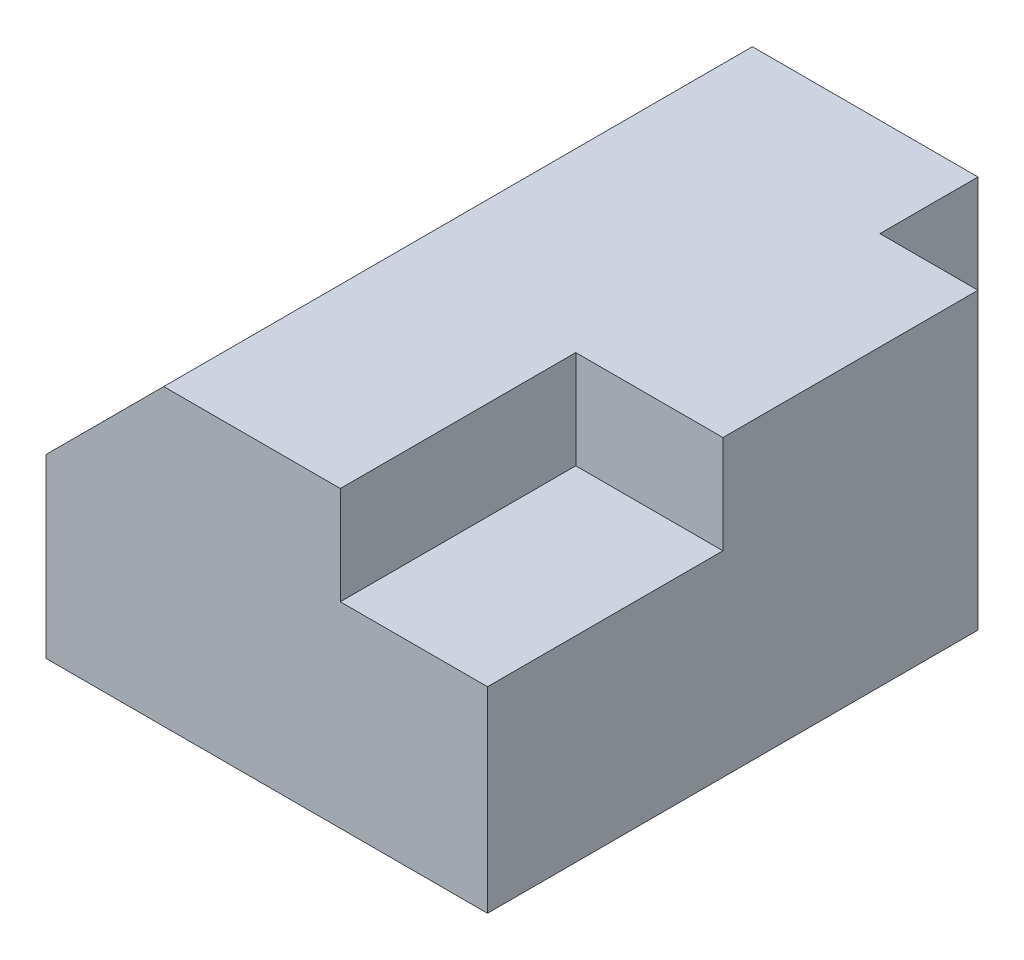
SolidWorks part; units mm, degrees
ref_plane "Front Plane" through (0, 0, 0) normal (0, 0, 1) x (1, 0, 0)
ref_plane "Top Plane" through (0, 0, 0) normal (0, 1, 0) x (1, 0, 0)
ref_plane "Right Plane" through (0, 0, 0) normal (1, 0, 0) x (0, 0, -1)
sketch "Sketch1" plane through (0, 0, 0) normal (0, 0, 1) x (1, 0, 0)
  line L0 (-22.0442, 13.663) -> (-22.0442, -4.337)
  line L1 (-22.0442, -4.337) -> (22.9558, -4.337)
  line L2 (22.9558, -4.337) -> (22.9558, 15.663)
  line L3 (22.9558, 15.663) -> (7.9558, 15.663)
  line L4 (7.9558, 15.663) -> (7.9558, 25.663)
  line L6 (7.9558, 25.663) -> (-10.0442, 25.663)
  line L7 (-10.0442, 25.663) -> (-22.0442, 13.663)
  point P2 (0, 0)
  point P8 (0, 0)
  point P9 (-10.7789, 25.0507)
  point P10 (-23.3702, 14.5028)
  point P14 (0.3315, 25.663)
  dimension "D1" = 18
  dimension "D2" = 45
  dimension "D3" = 20
  dimension "D4" = 10
  dimension "D5" = 12
  dimension "D6" = 18
  dimension "D7" = 22.0442
  dimension "D8" = 25.663
extrude "Boss-Extrude1" add sketch "Sketch1" along normal blind 60
sketch "Sketch3" plane through (0, 15.663, 0) normal (0, 1, 0) x (1, 0, 0)
  line L0 (22.9558, 0) -> (7.9558, 0)
  line L1 (7.9558, 0) -> (7.9558, -36)
  line L2 (7.9558, -60) -> (7.9558, 0) construction
  line L3 (7.9558, -36) -> (22.9558, -36)
  line L4 (22.9558, -60) -> (22.9558, 0) construction
  line L5 (22.9558, -36) -> (22.9558, 0)
  dimension "D1" = 36
extrude "Boss-Extrude2" add sketch "Sketch3" along normal blind 10
sketch "Sketch4" plane through (0, 25.663, 0) normal (0, 1, 0) x (1, 0, 0)
  line L0 (22.9558, 0) -> (12.9558, 0)
  line L1 (22.9558, 0) -> (-10.0442, 0) construction
  line L2 (12.9558, 0) -> (12.9558, -10)
  line L3 (12.9558, -10) -> (22.9558, -10)
  line L4 (22.9558, -36) -> (22.9558, 0) construction
  line L5 (22.9558, -10) -> (22.9558, 0)
  dimension "D1" = 10
  dimension "D2" = 10
extrude "Cut-Extrude2" cut sketch "Sketch4" against normal blind 40
